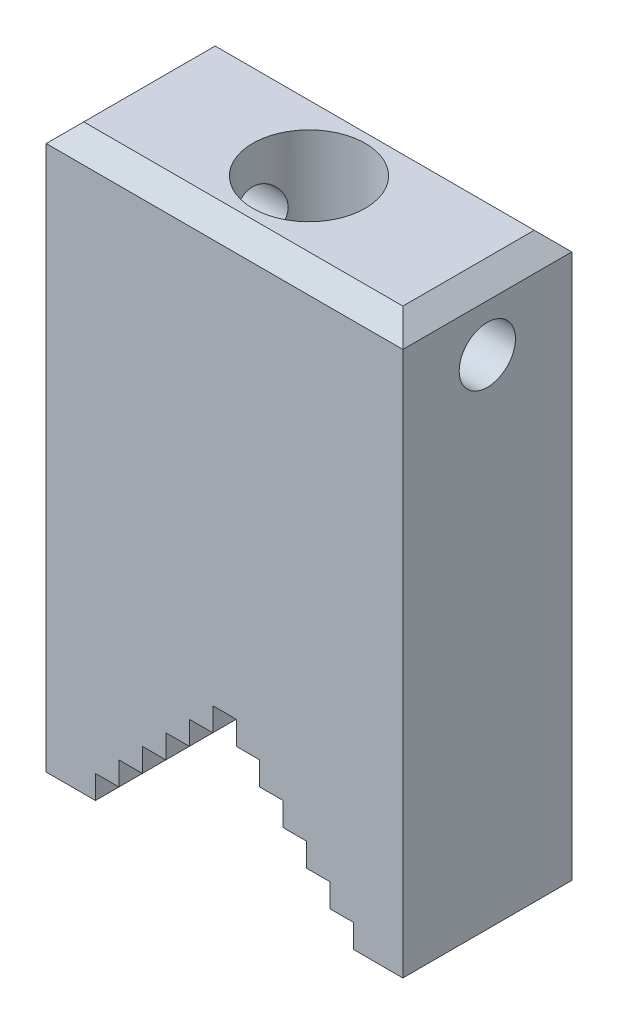
SolidWorks part; units mm, degrees
ref_plane "Front Plane" through (0, 0, 0) normal (0, 0, 1) x (1, 0, 0)
ref_plane "Top Plane" through (0, 0, 0) normal (0, 1, 0) x (1, 0, 0)
ref_plane "Right Plane" through (0, 0, 0) normal (1, 0, 0) x (0, 0, -1)
sketch "Sketch1" plane through (0, 0, 0) normal (0, 0, 1) x (1, 0, 0)
  line L0 (0, 30) -> (0, -37.5402) construction
  line L1 (-19, 30) -> (19, 30)
  line L2 (19, 30) -> (19, -30)
  line L3 (-19, 30) -> (-19, -30)
  line L4 (19, -30) -> (13.75, -30)
  line L5 (-19, -30) -> (-13.75, -30)
  line L6 (13.75, -30) -> (13.75, -27.5)
  line L7 (-13.75, -30) -> (-13.75, -27.5)
  line L8 (13.75, -27.5) -> (11.25, -27.5)
  line L9 (-13.75, -27.5) -> (-11.25, -27.5)
  line L10 (11.25, -27.5) -> (11.25, -25)
  line L11 (-11.25, -27.5) -> (-11.25, -25)
  line L12 (11.25, -25) -> (8.75, -25)
  line L13 (-11.25, -25) -> (-8.75, -25)
  line L14 (8.75, -25) -> (8.75, -22.5)
  line L15 (-8.75, -25) -> (-8.75, -22.5)
  line L16 (8.75, -22.5) -> (6.25, -22.5)
  line L17 (-8.75, -22.5) -> (-6.25, -22.5)
  line L18 (6.25, -22.5) -> (6.25, -20)
  line L19 (-6.25, -22.5) -> (-6.25, -20)
  line L20 (6.25, -20) -> (3.75, -20)
  line L21 (-6.25, -20) -> (-3.75, -20)
  line L22 (3.75, -20) -> (3.75, -17.5)
  line L23 (-3.75, -20) -> (-3.75, -17.5)
  line L24 (3.75, -17.5) -> (1.25, -17.5)
  line L25 (-3.75, -17.5) -> (-1.25, -17.5)
  line L26 (1.25, -17.5) -> (1.25, -15)
  line L27 (-1.25, -17.5) -> (-1.25, -15)
  line L28 (1.25, -15) -> (-1.25, -15)
  line L29 (-26.6068, 0) -> (38.3166, 0) construction
  line L30 (26.6068, 0) -> (-38.3166, 0) construction
  point P32 (0, -15)
  dimension "D1" = 27.5
  dimension "D2" = 38
  dimension "D3" = 60
  dimension "D4" = 15
  dimension "D5" = 2.5
  dimension "D6" = 2.5
extrude "Boss-Extrude1" add sketch "Sketch1" along normal mid plane 18
sketch "Sketch3" plane through (0, 30, 0) normal (0, 1, 0) x (1, 0, 0)
  point P0 (0, 0)
hole_wizard "Ø12.0mm Dowel Hole1" positions "3DSketch3" profile "Sketch5" hole size "Ø12.0" standard "ANSI Metric"
sketch3d "3DSketch3"
  point P0 (-0.0203, 30, -0.0203)
sketch "Sketch5" plane through (-0.0203, 30, -0.0203) normal (1, 0, 0) x (0, 0, 1)
  line L0 (0, 0) -> (0, 22.0471)
  line L1 (0, 22.0471) -> (6, 18)
  line L2 (6, 18) -> (6, 0)
  line L5 (6, 0) -> (0, 0)
  line L10 (0, 22.0471) -> (-6, 18) construction
  line L11 (0, -6.35) -> (0, 107.95) construction
  dimension "Hole Dia." = 12
  dimension "Hole Depth" = 18
  dimension "Drill Angle" = 112
sketch "Sketch6" plane through (-19, 0, 0) normal (-1, 0, 0) x (0, 0, 1)
  line L0 (9, 30) -> (-9, 30) construction
  line L1 (9, 30) -> (9, -30) construction
  circle A0 centre (0, 23) radius 3
  dimension "D1" = 6
  dimension "D2" = 7
  dimension "D3" = 9
extrude "Cut-Extrude1" cut sketch "Sketch6" against normal through all
chamfer "Chamfer1" distance 2 angle 45 4 edges at (19, 30, 0) (0, 30, 9) (-19, 30, 0) (0, 30, -9)
